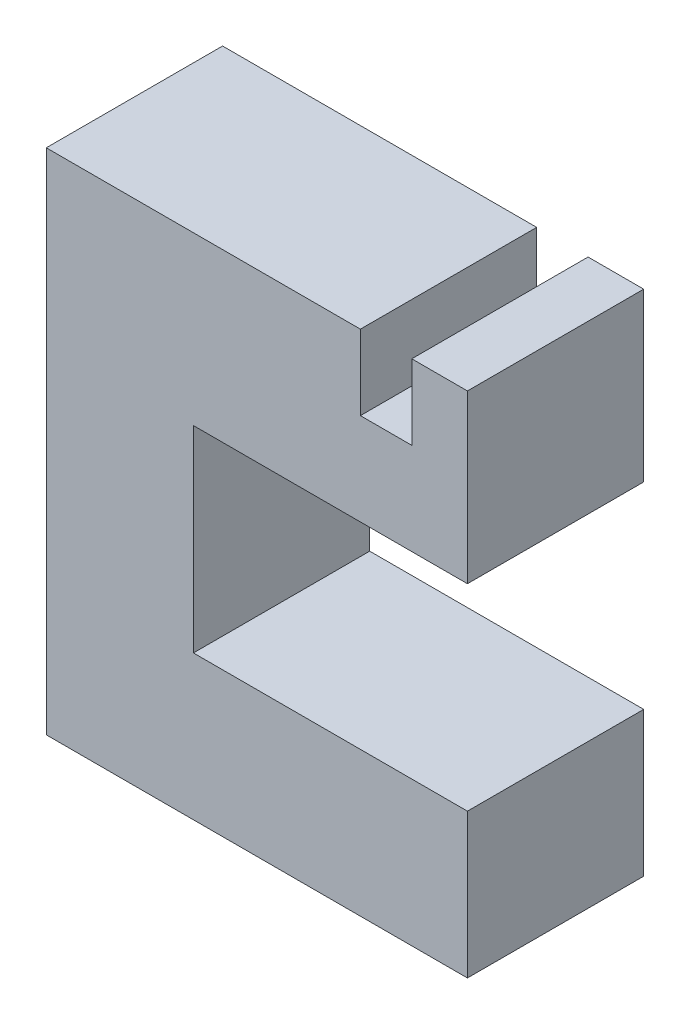
SolidWorks part; units mm, degrees
ref_plane "Plan de face" through (0, 0, 0) normal (0, 0, 1) x (1, 0, 0)
ref_plane "Plan de dessus" through (0, 0, 0) normal (0, 1, 0) x (1, 0, 0)
ref_plane "Plan de droite" through (0, 0, 0) normal (1, 0, 0) x (0, 0, -1)
sketch "Esquisse1" plane through (0, 0, 0) normal (0, 0, 1) x (1, 0, 0)
  line L0 (47.777, 57.6786) -> (47.777, 38.7357)
  line L1 (0, 0) -> (47.777, 0)
  line L2 (0, 0) -> (0, 57.6786)
  line L5 (47.777, 38.7357) -> (16.6913, 38.7357)
  line L6 (16.6913, 38.7357) -> (16.6913, 16.3929)
  line L7 (16.6913, 16.3929) -> (47.777, 16.3929)
  line L8 (47.777, 16.3929) -> (47.777, 0)
  line L9 (0, 57.6786) -> (35.6342, 57.6786)
  line L10 (35.6342, 57.6786) -> (35.6342, 49.1786)
  line L11 (35.6342, 49.1786) -> (41.4627, 49.1786)
  line L12 (41.4627, 49.1786) -> (41.4627, 57.6786)
  line L13 (41.4627, 57.6786) -> (47.777, 57.6786)
extrude "Boss.-Extru.1" add sketch "Esquisse1" along normal blind 20
